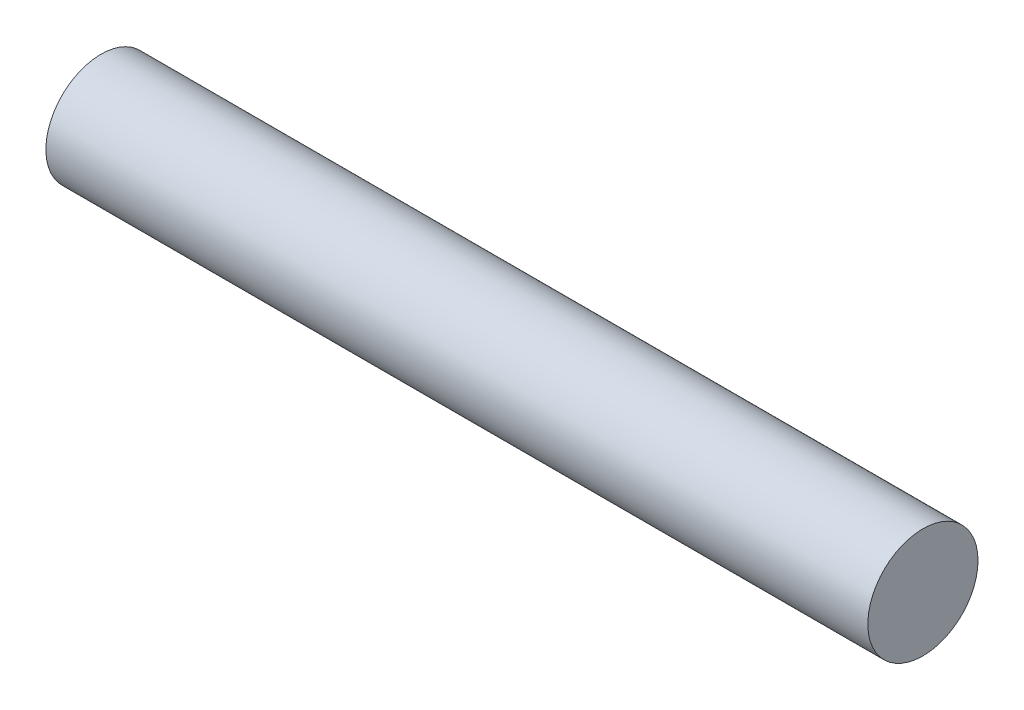
SolidWorks part; units mm, degrees
material "Custom Plastic"
ref_plane "X-Y Datum" through (0, 0, 0) normal (0, 0, 1) x (1, 0, 0)
ref_plane "X-Z Datum" through (0, 0, 0) normal (0, 1, 0) x (1, 0, 0)
ref_plane "Y-Z Datum" through (0, 0, 0) normal (1, 0, 0) x (0, 0, -1)
sketch3d "3DSketch2"
  line L0 (-69.0905, 97.75, 219.825) -> (-21.7215, 97.75, 219.825)
  circle A0 centre (-69.0905, 97.75, 219.825) radius 4.5 construction
  circle A3 centre (-21.7215, 97.75, 219.825) radius 4.5 construction
  point P4 (-64.5905, 97.75, 219.825)
  point P7 (-26.2215, 97.75, 219.825)
sweep "Sweep1" add path "3DSketch2" circular profile diameter 6.35 parameters "D3"=6.35
